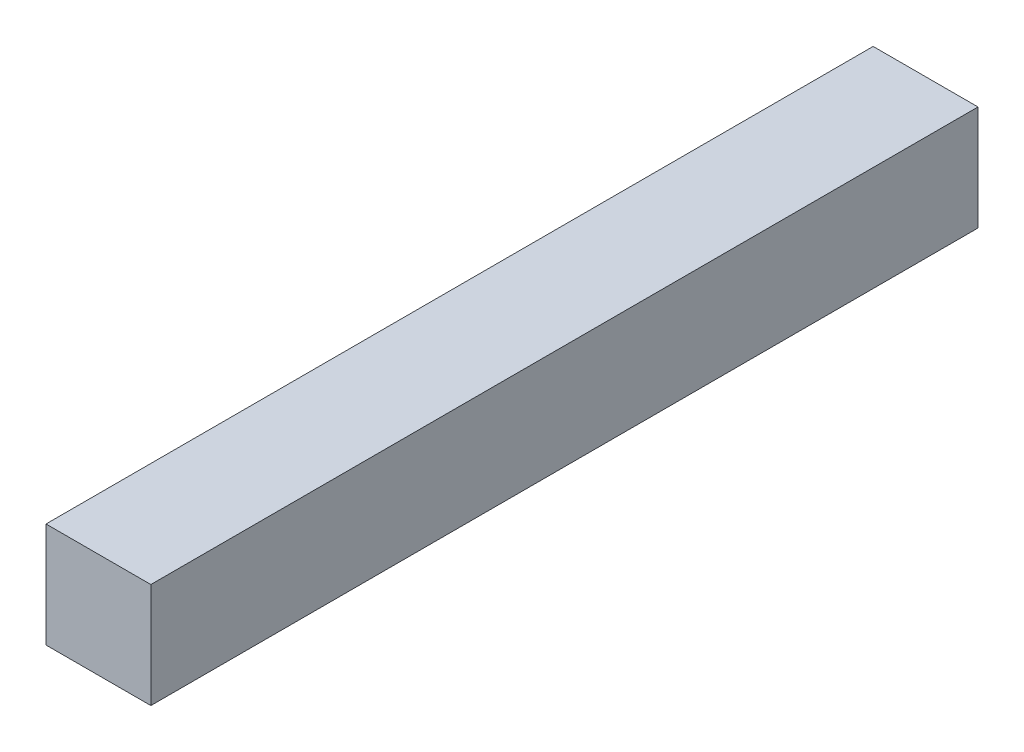
SolidWorks part; units mm, degrees
ref_plane "Front Plane" through (0, 0, 0) normal (0, 0, 1) x (1, 0, 0)
ref_plane "Top Plane" through (0, 0, 0) normal (0, 1, 0) x (1, 0, 0)
ref_plane "Right Plane" through (0, 0, 0) normal (1, 0, 0) x (0, 0, -1)
sketch "Sketch1" plane through (0, 0, 0) normal (0, 0, 1) x (1, 0, 0)
  line L0 (-500, -9) -> (-500, 9) construction
  line L1 (-339, 9) -> (-321, 9)
  line L2 (-339, 9) -> (-339, -9)
  line L3 (-339, -9) -> (-321, -9)
  line L4 (-321, 9) -> (-321, -9)
  line L5 (-339, 9) -> (-321, -9) construction
  line L6 (-339, -9) -> (-321, 9) construction
  point P0 (-330, 0)
  point P7 (0, 0)
extrude "Boss-Extrude1" add sketch "Sketch1" along normal up to surface (142 mm away)
